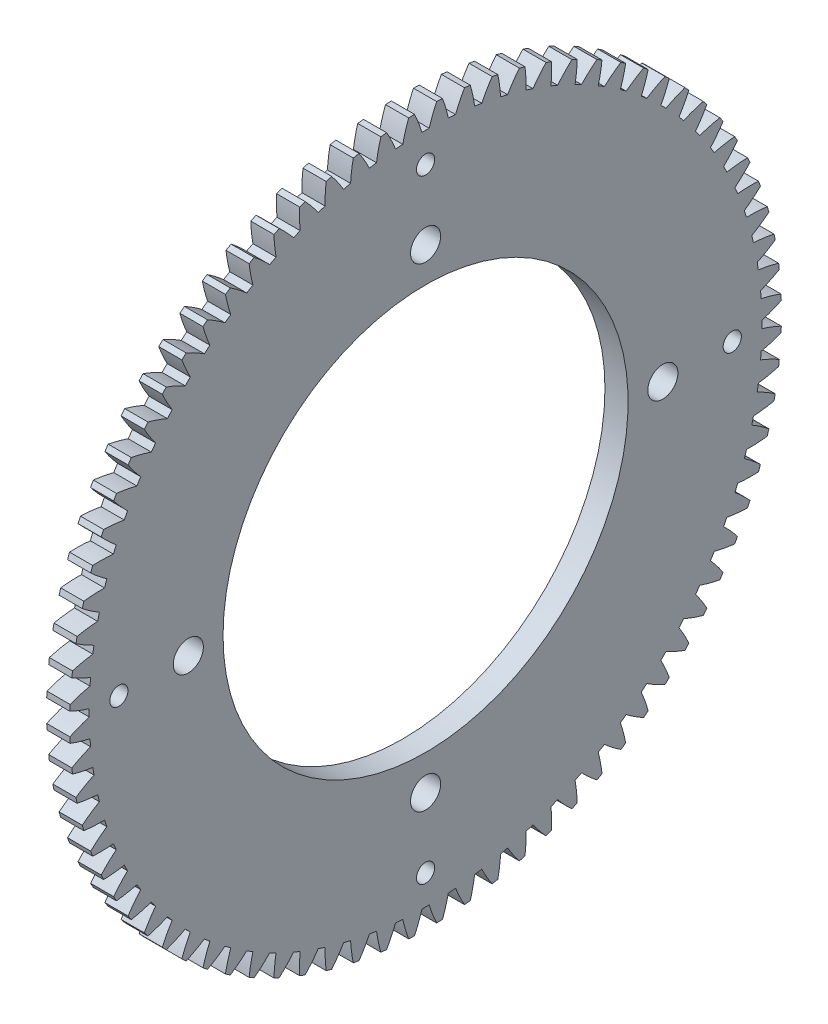
SolidWorks part; units mm, degrees
ref_plane "Plane1" through (0, 0, 0) normal (0, 0, 1) x (1, 0, 0)
ref_plane "Plane2" through (0, 0, 0) normal (0, 1, 0) x (1, 0, 0)
ref_plane "Plane3" through (0, 0, 0) normal (1, 0, 0) x (0, 0, -1)
other "Configuration Table"
sketch "HoldingSke" plane through (0, 0, 0) normal (0, 1, 0) x (1, 0, 0)
  line L0 (0, 0) -> (0.1158, -0.6565)
  line L1 (-15, 0) -> (100, 0) construction
  line L2 (0, 0) -> (-2.1039, 2.3779)
  line L3 (0, 0) -> (-11.863, 4.5341)
  line L4 (0, 0) -> (1.4996, 8.5048)
  line L5 (0, 0) -> (-46.8476, -17.4728)
  line L6 (0, 0) -> (-3.3159, -2.2372)
  line L7 (-2.1039, 2.3779) -> (8.6586, 51.2059)
  line L8 (-76.2, 54.61) -> (-71.3, 54.61)
  line L9 (-71.009, 38.7566) -> (-53.1078, 45.2721)
  line L10 (-76.2, 71.12) -> (104.1128, 71.12)
  line L11 (0, 0) -> (-4, 0)
  line L12 (-76.2, 101.6) -> (-76.147, 101.6)
  line L13 (24.9733, 27.94) -> (52.9518, 28.4284)
  line L14 (24.9733, 27.94) -> (24.9743, 27.94)
  line L15 (24.9733, 27.94) -> (100.4006, 29.5858)
  line L16 (-63.627, -1.5) -> (-12.827, -1.5)
  circle A0 centre (0, 0) radius 35
  circle A1 centre (0, 0) radius 37.5
  circle A2 centre (0, 0) radius 37.5
  circle A3 centre (0, 0) radius 35
  dimension "MHD" = 75
  dimension "Hub_dia" = 75
  dimension "Bore" = 70
  dimension "MBD" = 70
  dimension "Num_teeth" = 80
  dimension "Pitch" = 0.6667
  dimension "Overall_len" = 50
  dimension "Show_teeth" = 80
  dimension "Thickness" = 4
  dimension "OAL" = 50.0001
  dimension "T_dim" = 4.9
  dimension "Ap" = 20
  dimension "H" = 19.05
  dimension "Pitch_radius" = 180.3128
  dimension "Width" = 4
  dimension "Backlash" = 0.053
  dimension "Addendum_fac" = 1
  dimension "Dedendum_fac" = 1.25
  dimension "Clearance_fac" = 0.25
  dimension "Dedendum_add" = 0.001
  dimension "Module" = 1.5
sketch "BasProSke" plane through (0, 0, 0) normal (0, 1, 0) x (1, 0, 0)
  line L0 (-10, 0) -> (60, 0) construction
  line L1 (0, 0) -> (0, 61.5)
  line L2 (0, 0) -> (4, 0)
  line L3 (4, 0) -> (4, 61.5)
  line L4 (4, 61.5) -> (0, 61.5)
  dimension "Thickness" = 4
  dimension "Diameter" = 123
revolve "Base-Revolve" add sketch "BasProSke" angle 360 about L0
sketch "TooCutSke" plane through (0, 0, 0) normal (1, 0, 0) x (0, 0, -1)
  line L1 (0, 0) -> (0, 107) construction
  line L2 (0, 0) -> (-1.2708, 59.9865) construction
  line L3 (0, 0) -> (-4.7104, 119.8879) construction
  line L4 (-1.2708, 59.9865) -> (-2.3552, 59.9439) construction
  arc A0 (0.6242, 58.1206) -> (-0.6242, 58.1206) centre (0, 0) ccw
  arc A1 (1.9247, 61.4953) -> (-1.9247, 61.4953) centre (0, 0) ccw
  circle A2 centre (0, 0) radius 60 construction
  circle A3 centre (0, 0) radius 56.3816 construction
  arc A4 (-0.6242, 58.1206) -> (-1.9247, 61.4953) centre (-23.6054, 51.2022) ccw
  arc A5 (1.9247, 61.4953) -> (0.6242, 58.1206) centre (23.6054, 51.2022) ccw
  dimension "Root_dia" = 116.248
  dimension "Overcut_dia" = 123.0508
  dimension "Pitch_dia" = 120
  dimension "Base_dia" = 112.7631
  dimension "Flank_rad" = 24
  dimension "Half_ang" = 2.25
  dimension "Half_CT" = 1.0853
extrude "ToothCut" cut sketch "TooCutSke" along normal through all
fillet "Breaks" [suppressed] radius 0.03
fillet "RootFillets" [suppressed] radius 0.376
pattern_circular "TeethCuts" count 80 every 4.5 about axis through (-10, 0, 0) along (1, 0, 0) of "ToothCut", "RootFillets", "Breaks"
sketch "HubNeaOneSke" plane through (0, 0, 0) normal (-1, 0, 0) x (0, 0, 1)
  circle A0 centre (0, 0) radius 37.5
  dimension "Diameter" = 75
extrude "HubNearOne" [suppressed] add sketch "HubNeaOneSke" along normal blind 46.0001
sketch "HubNeaBotSke" plane through (0, 0, 0) normal (-1, 0, 0) x (0, 0, 1)
  circle A0 centre (0, 0) radius 37.5
  dimension "Diameter" = 75
extrude "HubNearBoth" [suppressed] add sketch "HubNeaBotSke" along normal blind 23
ref_plane "FarPln" through (4, 0, 0) normal (1, 0, 0) x (0, 0, -1)
sketch "HubFarSke" plane through (4, 0, 0) normal (1, 0, 0) x (0, 0, -1)
  circle A0 centre (0, 0) radius 37.5
  dimension "Diameter" = 75
extrude "HubFar" [suppressed] add sketch "HubFarSke" along normal blind 23
sketch "BorSke" plane through (0, 0, 0) normal (1, 0, 0) x (0, 0, -1)
  circle A0 centre (0, 0) radius 35
  dimension "Diameter" = 70
extrude "Bore" cut sketch "BorSke" along normal mid plane 100.0001
sketch "KeySke" plane through (0, 0, 0) normal (1, 0, 0) x (0, 0, -1)
  line L0 (-10, 0) -> (-10, 39.9)
  line L1 (-10, 39.9) -> (10, 39.9)
  line L2 (10, 39.9) -> (10, 0)
  line L3 (0, 0) -> (0, 34) construction
  line L4 (-10, 0) -> (10, 0)
  dimension "Offset" = 39.9
  dimension "Width" = 20
extrude "Keyway" [suppressed] cut sketch "KeySke" along normal mid plane 100.0001
pattern_circular "Keyway2" [suppressed] count 2 every 90 about axis through (-10, 0, 0) along (1, 0, 0)
sketch "草图1" plane through (4, 0, 0) normal (1, 0, 0) x (0, 0, -1)
  circle A0 centre (0, 0) radius 60
  dimension "D1" = 120
sketch "草图2" plane through (4, 0, 0) normal (1, 0, 0) x (0, 0, -1)
  line L0 (0, 0) -> (0, 41) construction
  line L1 (0, 53) -> (0, 41) construction
  circle A0 centre (0, 41) radius 2.6
  circle A1 centre (41, 0) radius 2.6
  circle A2 centre (0, -41) radius 2.6
  circle A3 centre (-41, 0) radius 2.6
  circle A4 centre (0, 53) radius 1.575
  circle A5 centre (53, 0) radius 1.575
  circle A6 centre (0, -53) radius 1.575
  circle A7 centre (-53, 0) radius 1.575
  point P13 (0, 0)
  point P22 (0, 0)
  dimension "D1" = 5.2
  dimension "D4" = 3.15
  dimension "D2" = 41
  dimension "D5" = 12
  dimension "D3" = 4
  dimension "D6" = 4
extrude "切除-拉伸1" cut sketch "草图2" against normal through all
equation "' \"Module@HoldingSke\" = 6.35"
equation "' \"Num_teeth@HoldingSke\" = 12"
equation "' \"Ap@HoldingSke\" =  20"
equation "' \"Ap@HoldingSke\" = 20"
equation "' \"Width@HoldingSke\" = 0.5 * 25.4"
equation "' \"Hub_dia@HoldingSke\"= 1 * 25.4"
equation "' \"Hub_dia@HoldingSke\" = 1 * 25.4"
equation "' \"Overall_len@HoldingSke\" = 1.0 * 25.4"
equation "' \"Bore@HoldingSke\" = 0.75 * 25.4"
equation "' \"T_dim@HoldingSke\" = 0.1 * 25.4"
equation "' \"Width@KeySke\" = 0.25 * 25.4"
equation "' \"Show_teeth@HoldingSke\" = 13"
equation "' \"Backlash@HoldingSke\" = 0.009 * 25.4"
equation "' \"Addendum_fac@HoldingSke\" = 1.0"
equation "' \"Dedendum_fac@HoldingSke\" = 1.25"
equation "' \"Dedendum_add@HoldingSke\" = 0.00005 * 25.4"
equation "' \"Clearance_fac@HoldingSke\" = 0.25"
equation "\"Pitch@HoldingSke\" = 1 / \"Module@HoldingSke\""
equation "\"Overcut_dia@TooCutSke\" = (\"Num_teeth@HoldingSke\" + 2 * \"Addendum_fac@HoldingSke\") / \"Pitch@HoldingSke\" + 0.002 * 25.4"
equation "\"Pitch_dia@TooCutSke\" = \"Num_teeth@HoldingSke\" / \"Pitch@HoldingSke\""
equation "\"Base_dia@TooCutSke\" = \"Num_teeth@HoldingSke\" / \"Pitch@HoldingSke\" * cos((\"Ap@HoldingSke\"  * 3.14159265 / 180))"
equation "\"Root_dia@TooCutSke\" = (\"Num_teeth@HoldingSke\" + 2) / \"Pitch@HoldingSke\" - 2 * (\"Addendum_fac@HoldingSke\" + \"Dedendum_fac@HoldingSke\") / \"Pitch@HoldingSke\" - \"Dedendum_add@HoldingSke\" * 2"
equation "\"Half_ang@TooCutSke\" = 180 / \"Num_teeth@HoldingSke\""
equation "\"Half_CT@TooCutSke\" = \"Num_teeth@HoldingSke\" / \"Pitch@HoldingSke\" * sin((3.14159265 / 2 / \"Num_teeth@HoldingSke\")) / 2 - 7 * \"Backlash@HoldingSke\" / 4"
equation "\"Flank_rad@TooCutSke\" = \"Num_teeth@HoldingSke\" / \"Pitch@HoldingSke\" / 5"
equation "\"Radius@RootFillets\" = \"Clearance_fac@HoldingSke\" / \"Pitch@HoldingSke\" + \"Dedendum_add@HoldingSke\""
equation "\"Break_rad@Breaks\" = 0.02 / \"Pitch@HoldingSke\""
equation "\"Thickness@HoldingSke\" = \"Width@HoldingSke\""
equation "\"OAL@HoldingSke\" = \"Thickness@HoldingSke\""
equation "\"MHD@HoldingSke\" = (\"Num_teeth@HoldingSke\" + 2) / \"Pitch@HoldingSke\" - 2 * (\"Addendum_fac@HoldingSke\" + \"Dedendum_fac@HoldingSke\")  / \"Pitch@HoldingSke\" - \"Dedendum_add@HoldingSke\" * 2"
equation "\"MBD@HoldingSke\" = (\"Num_teeth@HoldingSke\" + 2) / \"Pitch@HoldingSke\" - 2 * (\"Addendum_fac@HoldingSke\" + \"Dedendum_fac@HoldingSke\")  / \"Pitch@HoldingSke\" - \"Dedendum_add@HoldingSke\" * 2 - 0.002 * 25.4"
equation "\"MHD@HoldingSke\" = ((sgn( \"MHD@HoldingSke\" - \"Hub_dia@HoldingSke\" )-1)*( \"MHD@HoldingSke\" - \"Hub_dia@HoldingSke\" ))/-2+ \"Hub_dia@HoldingSke\""
equation "\"MBD@HoldingSke\" = ((sgn( \"MBD@HoldingSke\" - \"Bore@HoldingSke\" )-1)*( \"MBD@HoldingSke\" - \"Bore@HoldingSke\" ))/-2+ \"Bore@HoldingSke\""
equation "\"OAL@HoldingSke\" = ((sgn( \"OAL@HoldingSke\" - \"Overall_len@HoldingSke\" )+1)*( \"OAL@HoldingSke\" - \"Overall_len@HoldingSke\" ))/2 + \"Overall_len@HoldingSke\" + 0.000002 * 25.4"
equation "\"Num_teeth@TeethCuts\" = int( \"Show_teeth@HoldingSke\" ) + 1"
equation "\"Num_teeth@TeethCuts\" = ((sgn( \"Num_teeth@TeethCuts\" - \"Num_teeth@HoldingSke\" )-1)*( \"Num_teeth@TeethCuts\" - \"Num_teeth@HoldingSke\" ))/-2+ \"Num_teeth@HoldingSke\""
equation "\"Num_teeth@TeethCuts\" = ((sgn( \"Num_teeth@TeethCuts\" - 2.0)+1)*( \"Num_teeth@TeethCuts\" - 2.0))/2 +2.0"
equation "\"Angle@TeethCuts\" = 360.0 / \"Num_teeth@HoldingSke\""
equation "\"Diameter@BasProSke\" = (\"Num_teeth@HoldingSke\" + 2 * \"Addendum_fac@HoldingSke\") / \"Pitch@HoldingSke\""
equation "\"Thickness@BasProSke\"  = \"Thickness@HoldingSke\""
equation "' \"Fillet_rad@BasProSke\" =  \"Thickness@HoldingSke\" * 0.05"
equation "' \"Fillet_rad@BasProSke\" = \"Thickness@HoldingSke\" * 0.05"
equation "\"MHD@HoldingSke\" = ((sgn( \"MHD@HoldingSke\" - \"Root_dia@TooCutSke\" )-1)*( \"MHD@HoldingSke\" - \"Root_dia@TooCutSke\" ))/-2+ \"Root_dia@TooCutSke\""
equation "\"Diameter@HubNeaOneSke\" = \"MHD@HoldingSke\""
equation "\"Length@HubNearOne\" = \"OAL@HoldingSke\" - \"Thickness@BasProSke\""
equation "\"Diameter@HubNeaBotSke\" = \"MHD@HoldingSke\""
equation "\"Length@HubNearBoth\" = ( \"OAL@HoldingSke\" - \"Thickness@BasProSke\" ) / 2.0"
equation "\"Thickness@FarPln\" = \"Thickness@BasProSke\""
equation "\"Diameter@HubFarSke\" = \"MHD@HoldingSke\""
equation "\"Length@HubFar\" = ( \"OAL@HoldingSke\" - \"Thickness@BasProSke\" ) / 2.0"
equation "\"Diameter@BorSke\" = \"MBD@HoldingSke\""
equation "\"D1@Bore\" = \"OAL@HoldingSke\" * 2.0"
equation "\"D1@Keyway\" = \"OAL@HoldingSke\" * 2.0"
equation "\"Offset@KeySke\" = \"T_dim@HoldingSke\" + \"MBD@HoldingSke\" / 2.0"
